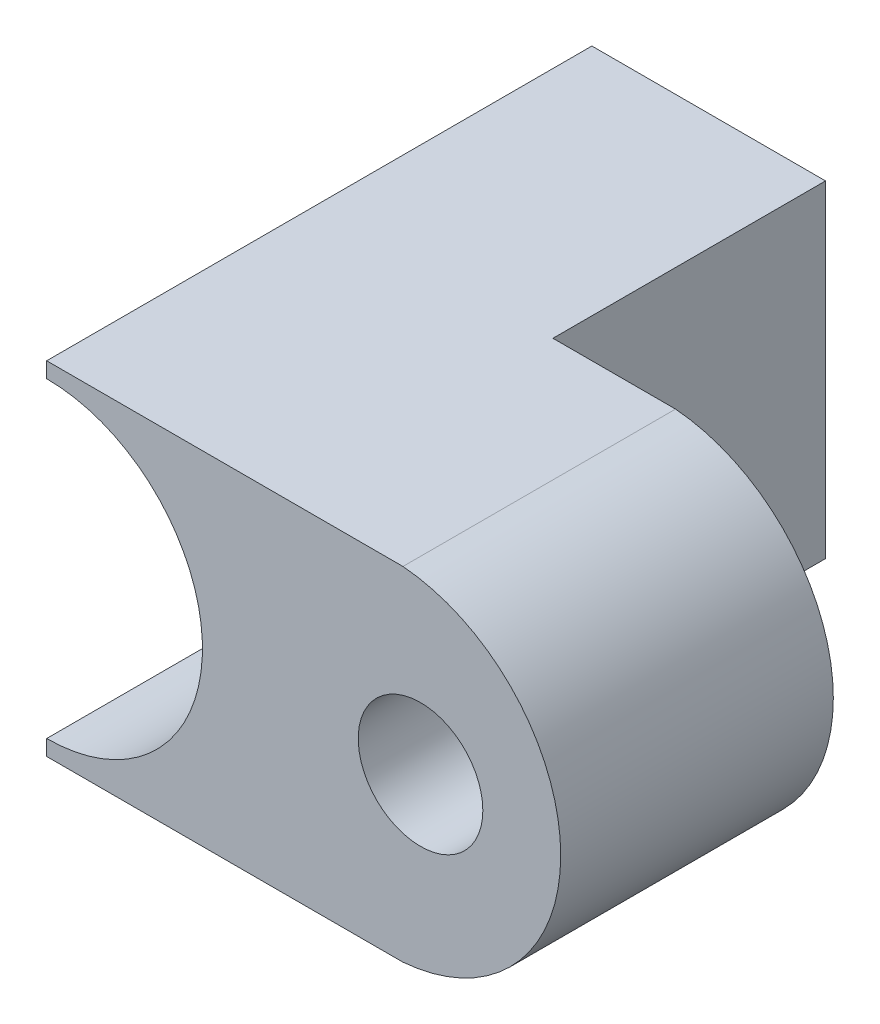
SolidWorks part; units mm, degrees
material "AISI Type A2 Tool Steel Custom"
ref_plane "Front Plane" through (0, 0, 0) normal (0, 0, 1) x (1, 0, 0)
ref_plane "Top Plane" through (0, 0, 0) normal (0, 1, 0) x (1, 0, 0)
ref_plane "Right Plane" through (0, 0, 0) normal (1, 0, 0) x (0, 0, -1)
sketch "Sketch1" plane through (0, 0, 0) normal (0, 0, 1) x (1, 0, 0)
  line L1 (0, -1.27) -> (29.0467, -1.27)
  line L3 (0, 26.67) -> (29.0467, 26.67)
  line L9 (0, 25.4) -> (0, 26.67)
  line L10 (0, 0) -> (0, -1.27)
  arc A1 (0, 0) -> (0, 25.4) centre (0, 12.7) ccw
  arc A4 (29.0467, -1.27) -> (29.0467, 26.67) centre (27.8924, 12.7) ccw
  point P3 (41.91, 12.7)
  dimension "D2" = 25.4
  dimension "D5" = 14.0176
  dimension "D3" = 41.91
  dimension "D1" = 1.27
  dimension "D4" = 1.27
extrude "Boss-Extrude1" add sketch "Sketch1" along normal blind 44.45
sketch "Sketch2" plane through (0, 0, 0) normal (0, 0, -1) x (-1, 0, 0)
  line L0 (-19.05, -1.27) -> (-19.05, 26.67)
  line L1 (0, -1.27) -> (-29.0467, -1.27) construction
  line L2 (-29.0467, 26.67) -> (0, 26.67) construction
  line L3 (0, -1.27) -> (-29.0467, -1.27) construction
  line L4 (-29.0467, 26.67) -> (0, 26.67) construction
  line L5 (-19.05, -1.27) -> (-29.0467, -1.27)
  line L10 (-29.0467, 26.67) -> (-19.05, 26.67)
  arc A1 (-29.0467, 26.67) -> (-29.0467, -1.27) centre (-27.8924, 12.7) ccw construction
  arc A3 (-29.0467, 26.67) -> (-29.0467, -1.27) centre (-27.8924, 12.7) ccw
  dimension "D1" = 19.05
extrude "Cut-Extrude1" cut sketch "Sketch2" against normal blind 22.225
sketch "Sketch3" plane through (0, 0, 44.45) normal (0, 0, 1) x (1, 0, 0)
  arc A0 (29.0467, -1.27) -> (29.0467, 26.67) centre (27.8924, 12.7) ccw construction
  point P0 (30.48, 12.7)
  point P13 (41.91, 12.7)
  dimension "D2" = 11.43
hole_wizard "3/8 (0.375) Diameter Hole1" positions "Sketch3" profile "Sketch4" hole size "3/8" standard "ANSI Inch" end condition through all
sketch "Sketch4" plane through (30.48, 12.7, 44.45) normal (1, 0, 0) x (0, -1, 0)
  line L0 (0, 0) -> (0, 44.45)
  line L1 (0, 44.45) -> (5.08, 44.45)
  line L2 (5.08, 44.45) -> (5.08, 0)
  line L5 (5.08, 0) -> (0, 0)
  line L11 (0, -6.35) -> (0, 107.95) construction
  dimension "Thru Hole Dia." = 10.16
  dimension "Thru Hole Depth" = 44.45
chamfer "Chamfer1" distance 1.27 angle 45 1 edges at (19.05, -1.27, 11.1125)
sketch "Sketch5" plane through (0, 0, 44.45) normal (0, 0, 1) x (1, 0, 0)
  arc A0 (29.0467, -1.27) -> (29.0467, 26.67) centre (27.8924, 12.7) ccw construction
  point P0 (41.91, 12.7)
